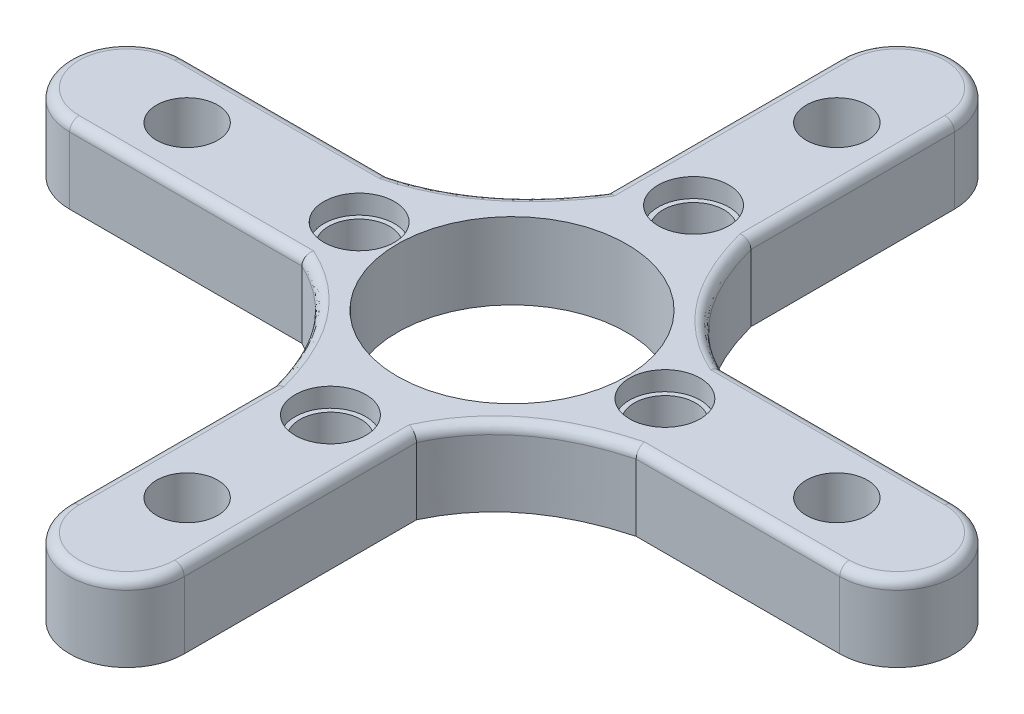
SolidWorks part; units mm, degrees
ref_plane "Alzado" through (0, 0, 0) normal (0, 0, 1) x (1, 0, 0)
ref_plane "Planta" through (0, 0, 0) normal (0, 1, 0) x (1, 0, 0)
ref_plane "Vista lateral" through (0, 0, 0) normal (1, 0, 0) x (0, 0, -1)
sketch "Croquis1" plane through (0, 0, 0) normal (0, 1, 0) x (1, 0, 0)
  line L0 (-3, 20.1513) -> (-3, 8)
  line L1 (3, 20.1513) -> (3, 9.5)
  line L2 (20.1513, 3) -> (8, 3)
  line L3 (20.1513, -3) -> (9.5, -3)
  line L4 (3, -20.1513) -> (3, -8)
  line L5 (-3, -20.1513) -> (-3, -9.5)
  line L6 (-20.1513, -3) -> (-8, -3)
  line L7 (-20.1513, 3) -> (-9.5, 3)
  line L8 (5.1225, 1.5788) -> (0.8775, 17.4212) construction
  line L9 (16.6447, -1.0311) -> (-0.6447, 7.0311) construction
  circle A0 centre (0, 0) radius 6
  circle A1 centre (8, 0) radius 2
  circle A2 centre (0, -9.5) radius 2
  circle A3 centre (-8, 0) radius 2
  circle A4 centre (0, 9.5) radius 2
  circle A5 centre (8, 0) radius 1.6
  circle A6 centre (0, 9.5) radius 1.6
  circle A7 centre (-8, 0) radius 1.6
  circle A8 centre (0, -9.5) radius 1.6
  circle A9 centre (0, 17) radius 1.6
  circle A10 centre (17, 0) radius 1.6
  circle A11 centre (0, -17) radius 1.6
  circle A12 centre (-17, 0) radius 1.6
  arc A13 (3, 20.1513) -> (-3, 20.1513) centre (0, 20.1513) ccw
  arc A14 (20.1513, -3) -> (20.1513, 3) centre (20.1513, 0) ccw
  arc A15 (-3, -20.1513) -> (3, -20.1513) centre (0, -20.1513) ccw
  arc A16 (-20.1513, 3) -> (-20.1513, -3) centre (-20.1513, 0) ccw
  spline S0 degree 3 poles (3, 9.5) (3.7075, 6.8596) (5.1184, 4.3437) (8, 3) knots 0 0 0 0 1 1 1 1
  spline S1 degree 3 poles (9.5, -3) (6.8596, -3.7075) (4.3437, -5.1184) (3, -8) knots 0 0 0 0 1 1 1 1
  spline S2 degree 3 poles (-3, -9.5) (-3.7075, -6.8596) (-5.1184, -4.3437) (-8, -3) knots 0 0 0 0 1 1 1 1
  spline S3 degree 2 poles (-9.5, 3) (-5.5394, 4.0612) (-3, 8) knots 0 0 0 1 1 1
  point P14 (0, 0)
  point P27 (0, 0)
  point P36 (17.5946, 0.5366)
  point P48 (0, 0)
  point P61 (0, 0)
  dimension "D1" = 12
  dimension "D2" = 4
  dimension "D7" = 3.2
  dimension "D8" = 3.2
  dimension "D9" = 3.2
  dimension "D10" = 3.2
  dimension "D11" = 3.2
  dimension "D13" = 3
  dimension "D15" = 15
  dimension "D3" = 9.5
  dimension "D4" = 9.5
  dimension "D5" = 8
  dimension "D6" = 17
  dimension "D12" = 17
  dimension "D14" = 4
  dimension "D16" = 25
extrude "Saliente-Extruir9" add sketch "Croquis1" along normal blind 4 contours S3 L7 A16 L6 S2 L5 A15 L4 S1 L3 A14 L2 S0 L1 A13 L0 A12 A11 A10 A9 A4 A2 A0 A3 A1 | A1 A5 | A3 A7 | A4 A6 | A2 A8
sketch "Croquis2" plane through (0, 4, 0) normal (0, 1, 0) x (1, 0, 0)
  circle A0 centre (0, 9.5) radius 1.85
  circle A1 centre (8, 0) radius 1.85
  circle A2 centre (0, -9.5) radius 1.85
  circle A3 centre (-8, 0) radius 1.85
  circle M22 centre (8, 0) radius 1.6
  circle M23 centre (-8, 0) radius 1.6
  circle M24 centre (0, -9.5) radius 1.6
  circle M25 centre (0, 9.5) radius 1.6
  dimension "D1" = 3.7
  dimension "D2" = 3.7
  dimension "D3" = 3.7
  dimension "D4" = 3.7
extrude "Cortar-Extruir6" cut sketch "Croquis2" against normal blind 1 contours A2 M24 | A0 M25 | A3 M23 | A1 M22
fillet "Redondeo1" radius 0.5 16 edges at (-3, 4, -14.0757) (0, 4, -23.1513) (3, 4, -14.8257) (14.0757, 4, -3) (23.1513, 4, 0) (14.8257, 4, 3) (3, 4, 14.0757) (0, 4, 23.1513) (-3, 4, 14.8257) (-14.0757, 4, 3) (-23.1513, 4, 0) (-14.8257, 4, -3)
